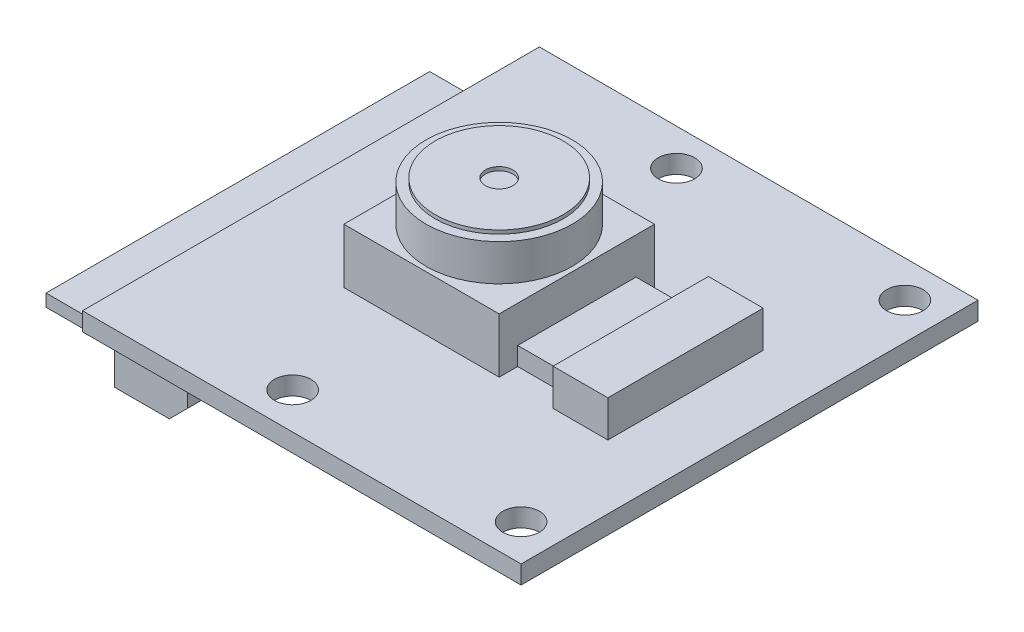
SolidWorks part; units mm, degrees
ref_plane "前视基准面" through (0, 0, 0) normal (0, 0, 1) x (1, 0, 0)
ref_plane "上视基准面" through (0, 0, 0) normal (0, 1, 0) x (1, 0, 0)
ref_plane "右视基准面" through (0, 0, 0) normal (1, 0, 0) x (0, 0, -1)
sketch "草图1" plane through (0, 0, 0) normal (0, 1, 0) x (1, 0, 0)
  line L1 (-12, 12.5) -> (12, 12.5)
  line L2 (-12, 12.5) -> (-12, -12.5)
  line L3 (-12, -12.5) -> (12, -12.5)
  line L4 (12, 12.5) -> (12, -12.5)
  line L5 (-12, 12.5) -> (12, -12.5) construction
  line L6 (-12, -12.5) -> (12, 12.5) construction
  point P0 (0, 0)
  dimension "D1" = 24
  dimension "D2" = 25
extrude "凸台-拉伸1" add sketch "草图1" along normal blind 1
sketch "草图2" plane through (0, 1, 0) normal (0, 1, 0) x (1, 0, 0)
  line L0 (-12, -12.5) -> (12, -12.5) construction
  line L1 (-5.95, -4.25) -> (2.55, -4.25)
  line L2 (-5.95, -4.25) -> (-5.95, 4.25)
  line L3 (-5.95, 4.25) -> (2.55, 4.25)
  line L4 (2.55, -4.25) -> (2.55, 4.25)
  line L5 (-5.95, -4.25) -> (2.55, 4.25) construction
  line L6 (-5.95, 4.25) -> (2.55, -4.25) construction
  line L9 (12, -12.5) -> (12, 12.5) construction
  point P0 (-1.7, 0)
  dimension "D1" = 12.5
  dimension "D2" = 13.7
  dimension "D3" = 8.5
  dimension "D4" = 8.5
extrude "凸台-拉伸2" add sketch "草图2" along normal blind 3
sketch "草图3" plane through (0, 4, 0) normal (0, 1, 0) x (1, 0, 0)
  line L0 (-5.95, -4.25) -> (2.55, -4.25) construction
  line L1 (2.55, -4.25) -> (2.55, 4.25) construction
  circle A0 centre (-1.7, 0) radius 4
  point P2 (0, 0)
  point P7 (-1.7, -4.25)
  point P8 (2.55, 0)
  dimension "D1" = 8
extrude "凸台-拉伸3" add sketch "草图3" along normal blind 2
sketch "草图4" plane through (0, 1, 0) normal (0, 1, 0) x (1, 0, 0)
  line L0 (12, -12.5) -> (12, 12.5) construction
  line L1 (5.5, -4.2542) -> (8.5, -4.2542)
  line L2 (5.5, -4.2542) -> (5.5, 4.2458)
  line L3 (5.5, 4.2458) -> (8.5, 4.2458)
  line L4 (8.5, -4.2542) -> (8.5, 4.2458)
  line L5 (5.5, -4.2542) -> (8.5, 4.2458) construction
  line L6 (5.5, 4.2458) -> (8.5, -4.2542) construction
  point P0 (7, -0.0042)
  dimension "D1" = 8.5
  dimension "D2" = 5
  dimension "D3" = 3
extrude "凸台-拉伸4" add sketch "草图4" along normal blind 2
sketch "草图5" plane through (0, 1, 0) normal (0, 1, 0) x (1, 0, 0)
  line L0 (2.55, -4.25) -> (2.55, 4.25) construction
  line L1 (2.55, 3.2381) -> (5.5, 3.2381)
  line L2 (2.55, 3.2381) -> (2.55, -3.2381)
  line L3 (2.55, -3.2381) -> (5.5, -3.2381)
  line L4 (5.5, 3.2381) -> (5.5, -3.2381)
  line L5 (5.5, 4.2458) -> (5.5, -4.2542) construction
extrude "凸台-拉伸5" add sketch "草图5" along normal blind 1
sketch "草图6" plane through (0, 0, 0) normal (0, 1, 0) x (1, 0, 0)
  line L0 (-12, -12.5) -> (12, -12.5) construction
  line L1 (-11, -11.75) -> (-7, -11.75)
  line L2 (-11, -11.75) -> (-11, 11.75)
  line L3 (-11, 11.75) -> (-7, 11.75)
  line L4 (-7, -11.75) -> (-7, 11.75)
  line L5 (-12, 12.5) -> (-12, -12.5) construction
  dimension "D1" = 23.5
  dimension "D2" = 0.75
  dimension "D3" = 4
  dimension "D4" = 1
extrude "凸台-拉伸6" add sketch "草图6" against normal blind 2.5
chamfer "倒角1" distance 1 angle 45 1 edges at (-7, -2.5, 0)
sketch "草图7" plane through (-11, 0, 0) normal (-1, 0, 0) x (0, 0, 1)
  line L1 (10.4968, -1.8365) -> (-10.4968, -1.8365)
  line L2 (10.4968, -1.8365) -> (10.4968, -1.1635)
  line L3 (10.4968, -1.1635) -> (-10.4968, -1.1635)
  line L4 (-10.4968, -1.8365) -> (-10.4968, -1.1635)
  line L5 (10.4968, -1.8365) -> (-10.4968, -1.1635) construction
  line L6 (10.4968, -1.1635) -> (-10.4968, -1.8365) construction
  point P0 (0, -1.5)
  dimension "D1" = 20.9936
  dimension "D2" = 0.673
extrude "凸台-拉伸7" add sketch "草图7" along normal blind 5
sketch "草图8" plane through (0, 1, 0) normal (0, 1, 0) x (1, 0, 0)
  line L0 (-12, -12.5) -> (12, -12.5) construction
  line L1 (12, -12.5) -> (12, 12.5) construction
  line L2 (12, 12.5) -> (-12, 12.5) construction
  circle A0 centre (10, -10.5) radius 1
  circle A1 centre (10, 10.5) radius 1
  circle A2 centre (-2.5, -10.5) radius 1
  circle A3 centre (-2.5, 10.5) radius 1
  dimension "D3" = 2
  dimension "D1" = 2
  dimension "D2" = 2
  dimension "D4" = 2
  dimension "D5" = 12.5
extrude "切除-拉伸1" cut sketch "草图8" against normal blind 1
sketch "草图9" plane through (0, 6, 0) normal (0, 1, 0) x (1, 0, 0)
  circle A0 centre (-1.7, 0) radius 3.5
  dimension "D1" = 7
extrude "凸台-拉伸8" add sketch "草图9" along normal blind 0.2
sketch "草图10" plane through (0, 6.2, 0) normal (0, 1, 0) x (1, 0, 0)
  circle A0 centre (-1.7, 0) radius 0.75
  dimension "D1" = 1.5
extrude "切除-拉伸2" cut sketch "草图10" against normal blind 0.2
